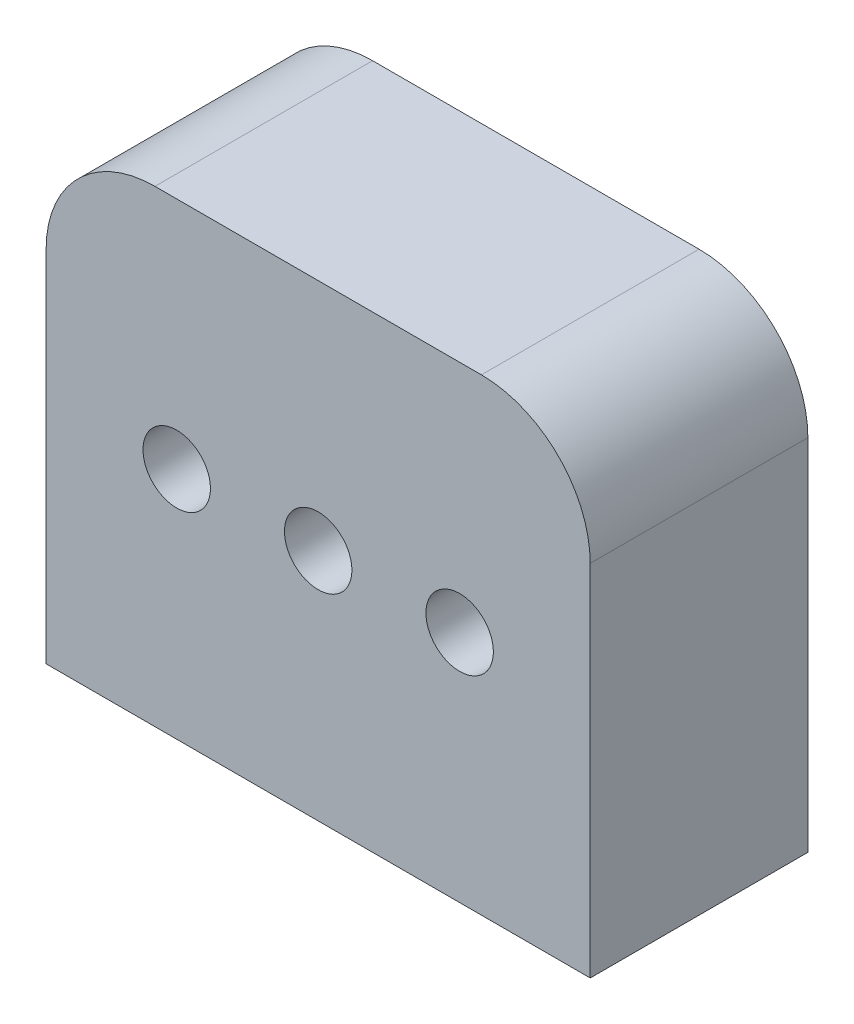
SolidWorks part; units mm, degrees
ref_plane "Front Plane" through (0, 0, 0) normal (0, 0, 1) x (1, 0, 0)
ref_plane "Top Plane" through (0, 0, 0) normal (0, 1, 0) x (1, 0, 0)
ref_plane "Right Plane" through (0, 0, 0) normal (1, 0, 0) x (0, 0, -1)
sketch "Sketch1" plane through (0, 0, 0) normal (0, 0, 1) x (1, 0, 0)
  line L1 (-6.35, 5.461) -> (6.35, 5.461)
  line L2 (-6.35, 5.461) -> (-6.35, -5.461)
  line L3 (-6.35, -5.461) -> (6.35, -5.461)
  line L4 (6.35, 5.461) -> (6.35, -5.461)
  line L5 (-6.35, 5.461) -> (6.35, -5.461) construction
  line L6 (-6.35, -5.461) -> (6.35, 5.461) construction
  point P0 (0, 0)
  dimension "D1" = 12.7
  dimension "D2" = 10.922
extrude "Boss-Extrude1" add sketch "Sketch1" along normal blind 5.08
sketch "Sketch2" plane through (0, 0, 0) normal (0, 0, 1) x (1, 0, 0)
  circle A0 centre (0, 0) radius 0.7874
  circle A1 centre (3.302, 0) radius 0.7874
  circle A2 centre (-3.302, 0) radius 0.7874
  dimension "D1" = 1.5748
  dimension "D2" = 1.5748
  dimension "D3" = 1.5748
  dimension "D4" = 3.302
  dimension "D5" = 3.302
extrude "Cut-Extrude1" cut sketch "Sketch2" along normal blind 5.08
fillet "Fillet1" radius 2.54 2 edges at (-6.35, 5.461, 2.54) (6.35, 5.461, 2.54)
